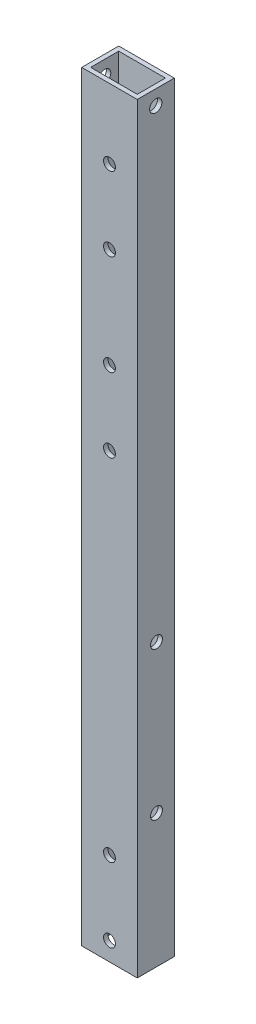
SolidWorks part; units mm, degrees
ref_plane "正面" through (0, 0, 0) normal (0, 0, 1) x (1, 0, 0)
ref_plane "平面" through (0, 0, 0) normal (0, 1, 0) x (1, 0, 0)
ref_plane "右側面" through (0, 0, 0) normal (1, 0, 0) x (0, 0, -1)
sketch "ｽｹｯﾁ1" plane through (0, 0, 0) normal (0, 1, 0) x (1, 0, 0)
  line L0 (-6.3, 3.8) -> (6.3, 3.8)
  line L1 (-7.5, 5) -> (7.5, 5)
  line L2 (-7.5, 5) -> (-7.5, -5)
  line L3 (-7.5, -5) -> (7.5, -5)
  line L4 (7.5, 5) -> (7.5, -5)
  line L5 (-7.5, 5) -> (7.5, -5) construction
  line L6 (-7.5, -5) -> (7.5, 5) construction
  line L7 (6.3, 3.8) -> (6.3, -3.8)
  line L8 (-6.3, -3.8) -> (6.3, -3.8)
  line L9 (-6.3, 3.8) -> (-6.3, -3.8)
  point P0 (0, 0)
  dimension "D1" = 15
  dimension "D2" = 10
  dimension "D3" = 1.2
extrude "ﾎﾞｽ - 押し出し1" add sketch "ｽｹｯﾁ1" along normal mid plane 220
sketch "ｽｹｯﾁ2" plane through (0, 0, -5) normal (0, 0, -1) x (-1, 0, 0)
  line L0 (0, -110) -> (0, -85) construction
  line L1 (-7.5, -110) -> (7.5, -110) construction
  circle A0 centre (0, -85) radius 1.6
  circle A1 centre (0, -105) radius 1.6
  dimension "D2" = 3.2
  dimension "D3" = 3.2
  dimension "D1" = 25
  dimension "D4" = 20
extrude "ｶｯﾄ - 押し出し1" cut sketch "ｽｹｯﾁ2" against normal blind 100
sketch "ｽｹｯﾁ3" plane through (-7.5, 0, 0) normal (-1, 0, 0) x (0, 0, 1)
  line L0 (0, -110) -> (0, 0) construction
  line L1 (-5, -110) -> (5, -110) construction
  circle A0 centre (-0.2, -74) radius 1.6
  circle A1 centre (-0.2, -34) radius 1.6
  dimension "D1" = 3.2
  dimension "D2" = 3.2
extrude "ｶｯﾄ - 押し出し2" cut sketch "ｽｹｯﾁ3" against normal blind 15
sketch "ｽｹｯﾁ5" plane through (0, 110, 0) normal (0, 1, 0) x (1, 0, 0)
  line L4 (7.5, -5) -> (7.5, 5)
  line L5 (7.5, 5) -> (-7.5, 5)
  line L6 (-7.5, 5) -> (-7.5, -5)
  line L7 (-7.5, -5) -> (7.5, -5)
  line L8 (7.5, -5) -> (7.5, 5)
  line L9 (7.5, 5) -> (-7.5, 5)
  line L10 (-7.5, 5) -> (-7.5, -5)
  line L11 (-7.5, -5) -> (7.5, -5)
  dimension "D1" = 0
extrude "ｶｯﾄ - 押し出し4" cut sketch "ｽｹｯﾁ5" against normal blind 14.5
sketch "ｽｹｯﾁ6" plane through (0, 0, -5) normal (0, 0, -1) x (-1, 0, 0)
  line L0 (0, 95.5) -> (0, 90.5) construction
  line L1 (-7.5, 95.5) -> (7.5, 95.5) construction
  line L2 (0, 90.5) -> (0, 76.66) construction
  line L3 (0, 76.66) -> (0, 56.66) construction
  circle A0 centre (0, 90.5) radius 1.6
  circle A1 centre (0, 76.66) radius 1.6
  circle A2 centre (0, 56.66) radius 1.6
  dimension "D2" = 3.2
  dimension "D4" = 3.2
  dimension "D6" = 3.2
  dimension "D1" = 5
  dimension "D3" = 13.84
  dimension "D5" = 20
extrude "ｶｯﾄ - 押し出し5" cut sketch "ｽｹｯﾁ6" against normal blind 15 contours A2 | A1
sketch "ｽｹｯﾁ7" plane through (-7.5, 0, 0) normal (-1, 0, 0) x (0, 0, 1)
  arc A0 (0, 93.15) -> (0, 89.85) centre (0, 91.5) ccw construction
  arc A1 (0, 89.85) -> (0, 93.15) centre (0, 91.5) ccw construction
  arc A2 (0, 93.15) -> (0, 89.85) centre (0, 91.5) ccw
  arc A3 (0, 89.85) -> (0, 93.15) centre (0, 91.5) ccw
extrude "ｶｯﾄ - 押し出し6" cut sketch "ｽｹｯﾁ7" against normal blind 15
sketch "ｽｹｯﾁ8" plane through (0, 0, -5) normal (0, 0, -1) x (-1, 0, 0)
  circle A0 centre (0, 9.6) radius 1.6 construction
  circle A1 centre (0, 29.6) radius 1.6 construction
  circle A2 centre (0, 9.6) radius 1.6
  circle A3 centre (0, 29.6) radius 1.6
extrude "ｶｯﾄ - 押し出し7" cut sketch "ｽｹｯﾁ8" against normal blind 10
